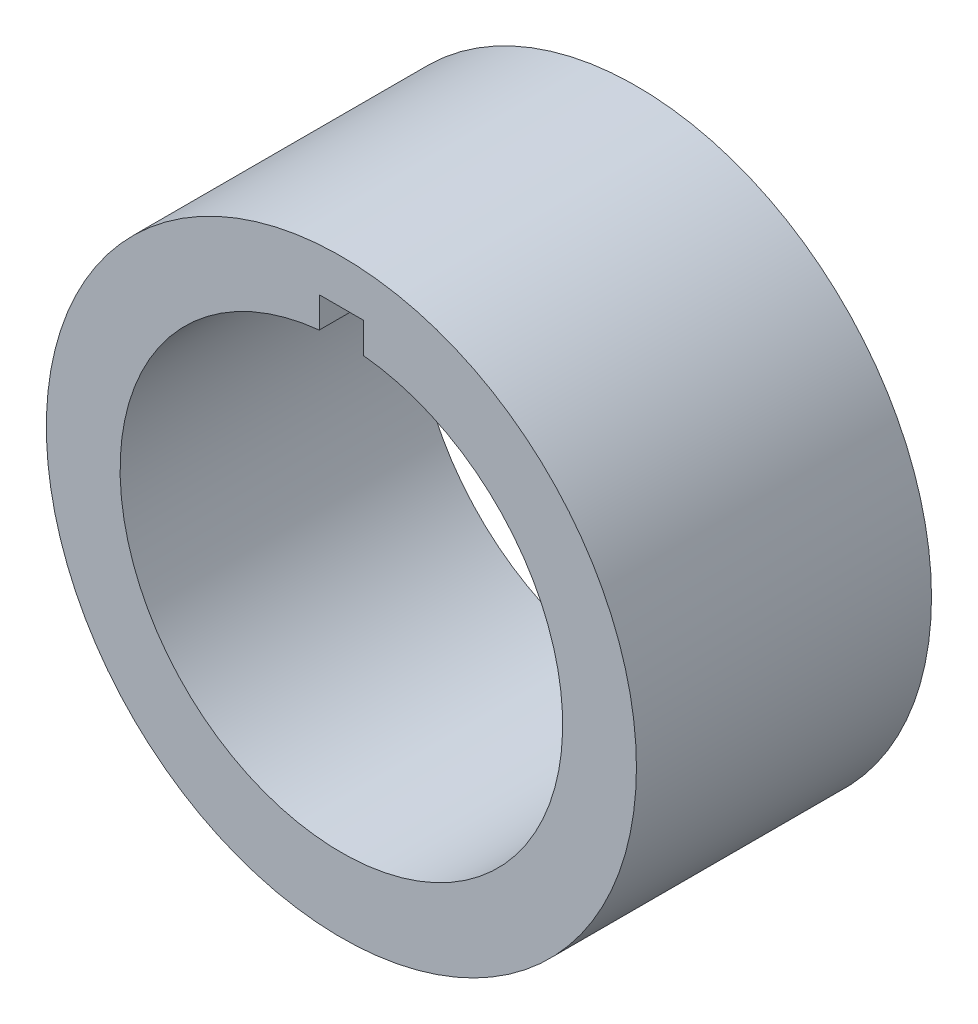
SolidWorks part; units mm, degrees
ref_plane "前视基准面" through (0, 0, 0) normal (0, 0, 1) x (1, 0, 0)
ref_plane "上视基准面" through (0, 0, 0) normal (0, 1, 0) x (1, 0, 0)
ref_plane "右视基准面" through (0, 0, 0) normal (1, 0, 0) x (0, 0, -1)
other "Configuration Table"
sketch "草图1" plane through (0, 0, 0) normal (0, 0, 1) x (1, 0, 0)
  circle A0 centre (0, 0) radius 20
  dimension "D1" = 40
extrude "凸台-拉伸1" add sketch "草图1" along normal blind 20
sketch "草图2" plane through (0, 0, 20) normal (0, 0, 1) x (1, 0, 0)
  line L1 (-1.5, 0) -> (1.5, 0)
  line L2 (-1.5, 0) -> (-1.5, 17)
  line L3 (-1.5, 17) -> (1.5, 17)
  line L4 (1.5, 0) -> (1.5, 17)
  circle A0 centre (0, 0) radius 15
  point P7 (0, 0)
  dimension "D1" = 30
  dimension "D2" = 17
  dimension "D3" = 3
extrude "切除-拉伸1" cut sketch "草图2" against normal through all contours L2 A0 L4 L1 | L4 A0 L2 L1
